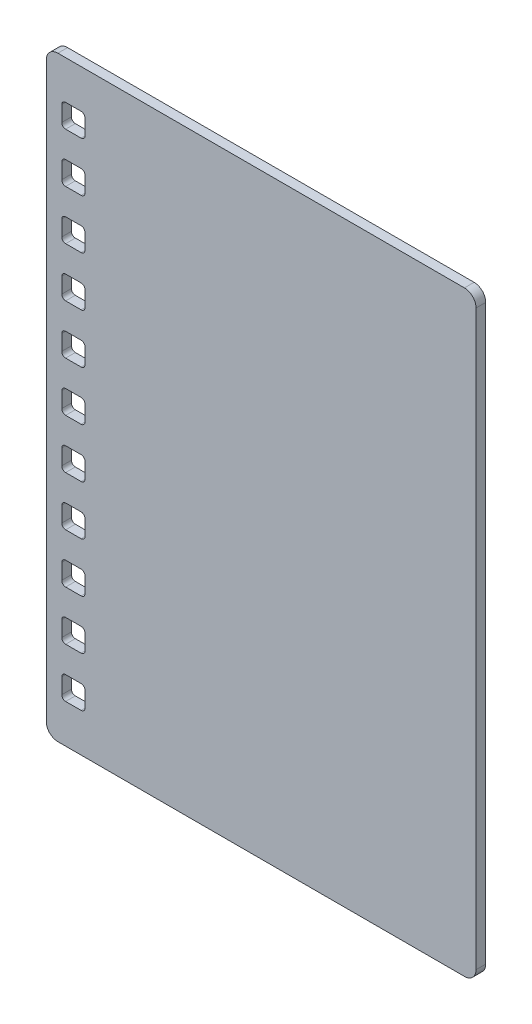
SolidWorks part; units mm, degrees
ref_plane "Front Plane" through (0, 0, 0) normal (0, 0, 1) x (1, 0, 0)
ref_plane "Top Plane" through (0, 0, 0) normal (0, 1, 0) x (1, 0, 0)
ref_plane "Right Plane" through (0, 0, 0) normal (1, 0, 0) x (0, 0, -1)
sketch "Sketch1" plane through (0, 0, 0) normal (0, 0, 1) x (1, 0, 0)
  line L0 (5, 22.8) -> (9, 22.8)
  line L1 (3, 0) -> (108, 0)
  line L2 (0, 3) -> (0, 151)
  line L3 (3, 154) -> (108, 154)
  line L4 (111, 3) -> (111, 151)
  line L5 (5, 16) -> (9, 16)
  line L6 (4, 15) -> (4, 11)
  line L7 (5, 10) -> (9, 10)
  line L8 (10, 15) -> (10, 11)
  line L9 (10, 27.8) -> (10, 23.8)
  line L10 (5, 28.8) -> (9, 28.8)
  line L11 (4, 27.8) -> (4, 23.8)
  line L12 (5, 35.6) -> (9, 35.6)
  line L13 (10, 40.6) -> (10, 36.6)
  line L14 (5, 41.6) -> (9, 41.6)
  line L15 (4, 40.6) -> (4, 36.6)
  line L16 (5, 48.4) -> (9, 48.4)
  line L17 (10, 53.4) -> (10, 49.4)
  line L18 (5, 54.4) -> (9, 54.4)
  line L19 (4, 53.4) -> (4, 49.4)
  line L20 (5, 61.2) -> (9, 61.2)
  line L21 (10, 66.2) -> (10, 62.2)
  line L22 (5, 67.2) -> (9, 67.2)
  line L23 (4, 66.2) -> (4, 62.2)
  line L24 (5, 74) -> (9, 74)
  line L25 (10, 79) -> (10, 75)
  line L26 (5, 80) -> (9, 80)
  line L27 (4, 79) -> (4, 75)
  line L28 (5, 86.8) -> (9, 86.8)
  line L29 (10, 91.8) -> (10, 87.8)
  line L30 (5, 92.8) -> (9, 92.8)
  line L31 (4, 91.8) -> (4, 87.8)
  line L32 (5, 99.6) -> (9, 99.6)
  line L33 (10, 104.6) -> (10, 100.6)
  line L34 (5, 105.6) -> (9, 105.6)
  line L35 (4, 104.6) -> (4, 100.6)
  line L36 (5, 112.4) -> (9, 112.4)
  line L37 (10, 117.4) -> (10, 113.4)
  line L38 (5, 118.4) -> (9, 118.4)
  line L39 (4, 117.4) -> (4, 113.4)
  line L40 (5, 125.2) -> (9, 125.2)
  line L41 (10, 130.2) -> (10, 126.2)
  line L42 (5, 131.2) -> (9, 131.2)
  line L43 (4, 130.2) -> (4, 126.2)
  line L44 (5, 138) -> (9, 138)
  line L45 (10, 143) -> (10, 139)
  line L46 (5, 144) -> (9, 144)
  line L47 (4, 143) -> (4, 139)
  arc A0 (10, 143) -> (9, 144) centre (9, 143) ccw
  arc A1 (5, 138) -> (4, 139) centre (5, 139) cw
  arc A2 (9, 138) -> (10, 139) centre (9, 139) ccw
  arc A3 (5, 144) -> (4, 143) centre (5, 143) ccw
  arc A4 (10, 130.2) -> (9, 131.2) centre (9, 130.2) ccw
  arc A5 (5, 125.2) -> (4, 126.2) centre (5, 126.2) cw
  arc A6 (9, 125.2) -> (10, 126.2) centre (9, 126.2) ccw
  arc A7 (5, 131.2) -> (4, 130.2) centre (5, 130.2) ccw
  arc A8 (10, 117.4) -> (9, 118.4) centre (9, 117.4) ccw
  arc A9 (5, 112.4) -> (4, 113.4) centre (5, 113.4) cw
  arc A10 (9, 112.4) -> (10, 113.4) centre (9, 113.4) ccw
  arc A11 (5, 118.4) -> (4, 117.4) centre (5, 117.4) ccw
  arc A12 (10, 104.6) -> (9, 105.6) centre (9, 104.6) ccw
  arc A13 (5, 99.6) -> (4, 100.6) centre (5, 100.6) cw
  arc A14 (9, 99.6) -> (10, 100.6) centre (9, 100.6) ccw
  arc A15 (5, 105.6) -> (4, 104.6) centre (5, 104.6) ccw
  arc A16 (10, 91.8) -> (9, 92.8) centre (9, 91.8) ccw
  arc A17 (5, 86.8) -> (4, 87.8) centre (5, 87.8) cw
  arc A18 (9, 86.8) -> (10, 87.8) centre (9, 87.8) ccw
  arc A19 (5, 92.8) -> (4, 91.8) centre (5, 91.8) ccw
  arc A20 (10, 79) -> (9, 80) centre (9, 79) ccw
  arc A21 (5, 74) -> (4, 75) centre (5, 75) cw
  arc A22 (9, 74) -> (10, 75) centre (9, 75) ccw
  arc A23 (5, 80) -> (4, 79) centre (5, 79) ccw
  arc A24 (10, 66.2) -> (9, 67.2) centre (9, 66.2) ccw
  arc A25 (5, 61.2) -> (4, 62.2) centre (5, 62.2) cw
  arc A26 (9, 61.2) -> (10, 62.2) centre (9, 62.2) ccw
  arc A27 (5, 67.2) -> (4, 66.2) centre (5, 66.2) ccw
  arc A28 (10, 53.4) -> (9, 54.4) centre (9, 53.4) ccw
  arc A29 (5, 48.4) -> (4, 49.4) centre (5, 49.4) cw
  arc A30 (9, 48.4) -> (10, 49.4) centre (9, 49.4) ccw
  arc A31 (5, 54.4) -> (4, 53.4) centre (5, 53.4) ccw
  arc A32 (10, 40.6) -> (9, 41.6) centre (9, 40.6) ccw
  arc A33 (5, 35.6) -> (4, 36.6) centre (5, 36.6) cw
  arc A34 (9, 35.6) -> (10, 36.6) centre (9, 36.6) ccw
  arc A35 (5, 41.6) -> (4, 40.6) centre (5, 40.6) ccw
  arc A36 (10, 27.8) -> (9, 28.8) centre (9, 27.8) ccw
  arc A37 (5, 22.8) -> (4, 23.8) centre (5, 23.8) cw
  arc A38 (9, 22.8) -> (10, 23.8) centre (9, 23.8) ccw
  arc A39 (5, 28.8) -> (4, 27.8) centre (5, 27.8) ccw
  arc A40 (9, 16) -> (10, 15) centre (9, 15) cw
  arc A41 (4, 11) -> (5, 10) centre (5, 11) ccw
  arc A42 (9, 10) -> (10, 11) centre (9, 11) ccw
  arc A43 (5, 16) -> (4, 15) centre (5, 15) ccw
  arc A44 (3, 0) -> (0, 3) centre (3, 3) cw
  arc A45 (108, 0) -> (111, 3) centre (108, 3) ccw
  arc A46 (0, 151) -> (3, 154) centre (3, 151) cw
  arc A47 (108, 154) -> (111, 151) centre (108, 151) cw
  point P131 (10, 16)
  point P136 (10, 10)
  point P139 (4, 16)
  point P142 (0, 0)
  point P145 (111, 0)
  point P150 (111, 154)
  dimension "D8" = 1
  dimension "D9" = 3
  dimension "D1" = 154
  dimension "D2" = 111
  dimension "D3" = 10
  dimension "D4" = 4
  dimension "D5" = 6
  dimension "D6" = 6
  dimension "D7" = 11
extrude "Boss-Extrude1" add sketch "Sketch1" along normal blind 2.5
